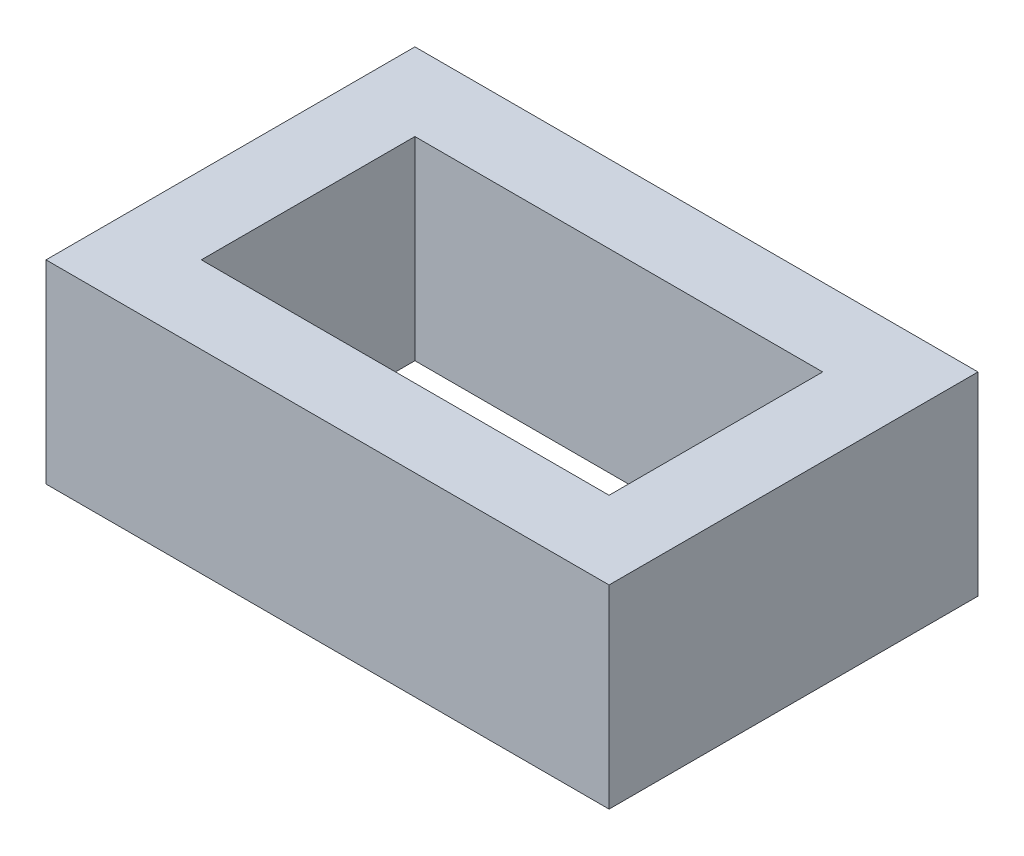
SolidWorks part; units mm, degrees
ref_plane "Front Plane" through (0, 0, 0) normal (0, 0, 1) x (1, 0, 0)
ref_plane "Top Plane" through (0, 0, 0) normal (0, 1, 0) x (1, 0, 0)
ref_plane "Right Plane" through (0, 0, 0) normal (1, 0, 0) x (0, 0, -1)
sketch "Sketch1" plane through (0, 0, 0) normal (0, 1, 0) x (1, 0, 0)
  line L0 (-7.25, 4.75) -> (-7.25, -4.75)
  line L5 (-9, -4.7143) -> (9, 4.7143) construction
  line L6 (-9, 4.7143) -> (9, -4.7143) construction
  line L7 (-5.25, 2.75) -> (5.25, 2.75)
  line L8 (-5.25, 2.75) -> (-5.25, -2.75)
  line L9 (-5.25, -2.75) -> (5.25, -2.75)
  line L10 (5.25, 2.75) -> (5.25, -2.75)
  line L11 (-5.25, 2.75) -> (5.25, -2.75) construction
  line L12 (-5.25, -2.75) -> (5.25, 2.75) construction
  line L13 (-7.25, -4.75) -> (7.25, -4.75)
  line L14 (7.25, 4.75) -> (7.25, -4.75)
  line L15 (-7.25, 4.75) -> (7.25, 4.75)
  point P0 (0, 0)
  point P6 (0, 0)
  dimension "D1" = 18
  dimension "D2" = 10.5
  dimension "D3" = 5.5
  dimension "D4" = 2
extrude "Boss-Extrude1" add sketch "Sketch1" along normal blind 5
